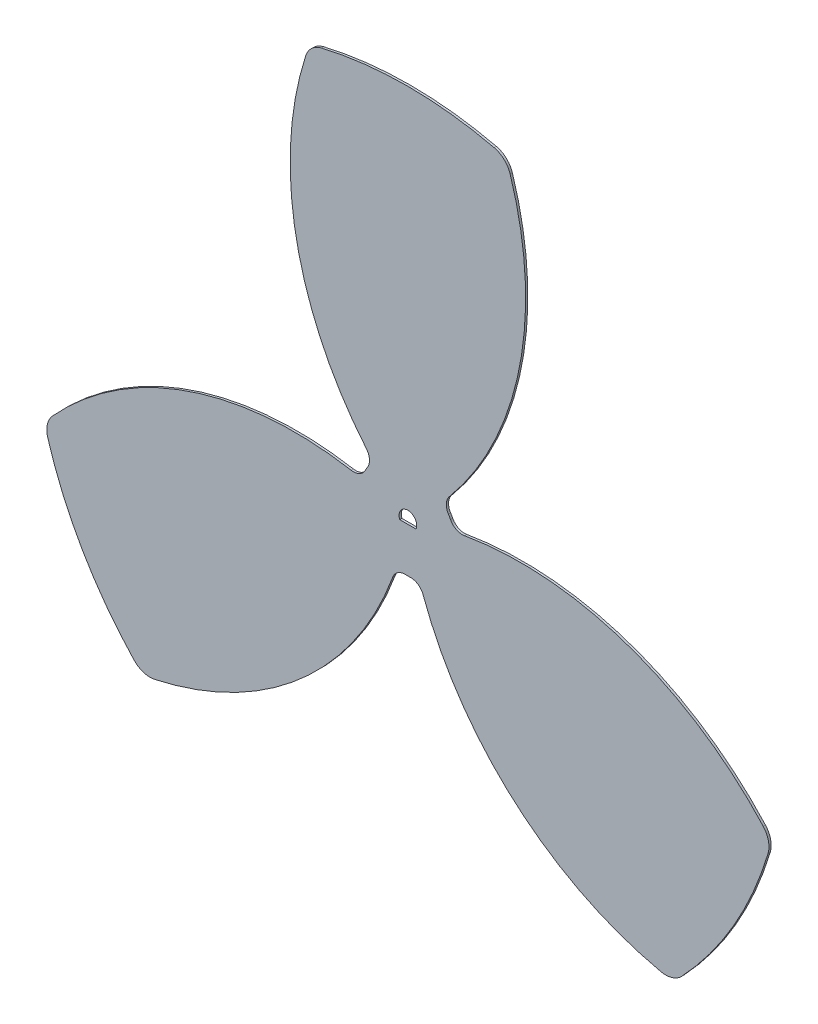
SolidWorks part; units mm, degrees
ref_plane "Plan de face" through (0, 0, 0) normal (0, 0, 1) x (1, 0, 0)
ref_plane "Plan de dessus" through (0, 0, 0) normal (0, 1, 0) x (1, 0, 0)
ref_plane "Plan de droite" through (0, 0, 0) normal (1, 0, 0) x (0, 0, -1)
sketch "Esquisse2" plane through (0, 0, 0) normal (0, 0, 1) x (1, 0, 0)
  line L0 (-43.229, 36.5855) -> (-43.229, 206.5855)
  circle A0 centre (-43.229, 36.5855) radius 21.7168
  arc A1 (1.1818, 200.682) -> (-87.6398, 200.682) centre (-43.229, 36.5855) ccw
  arc A2 (-87.6398, 200.682) -> (-43.229, 36.5855) centre (51.7427, 150.3464) ccw
  arc A3 (1.1818, 200.682) -> (-43.229, 36.5855) centre (-138.2007, 150.3464) cw
  arc A4 (121.0882, -7.0019) -> (-43.229, 36.5855) centre (7.805, -102.5428) ccw
  arc A5 (76.6774, -83.9237) -> (121.0882, -7.0019) centre (-43.229, 36.5855) ccw
  arc A6 (76.6774, -83.9237) -> (-43.229, 36.5855) centre (102.7767, 61.9529) cw
  arc A7 (-163.1354, -83.9237) -> (-43.229, 36.5855) centre (-189.2347, 61.9529) ccw
  arc A8 (-207.5462, -7.0019) -> (-163.1354, -83.9237) centre (-43.229, 36.5855) ccw
  arc A9 (-207.5462, -7.0019) -> (-43.229, 36.5855) centre (-94.263, -102.5428) cw
  point P18 (-43.229, 36.5855)
  dimension "D1" = 3
  dimension "D2" = 170
extrude "Boss.-Extru.1" add sketch "Esquisse2" along normal blind 1 contours A9 A8 A7 A0 | A6 A5 A4 A0 | A3 A1 L0 A0 | A1 A2 A0 L0 | A9 A0 A7 | A6 A0 A4 | A7 A0 A6 | A0 A9 A2 | A0 A2 L0 | A3 A0 L0 | A4 A0 A3
sketch "Esquisse4" plane through (0, 0, 0) normal (0, 0, -1) x (-1, 0, 0)
  line L0 (43.229, 14.8687) -> (43.229, 206.5855) construction
  line L1 (-103.9953, -48.4145) -> (62.0363, 47.4439) construction
  line L2 (46.9371, 35.0855) -> (39.5209, 35.0855)
  arc A0 (37.9538, 15.5192) -> (48.5042, 15.5192) centre (43.229, 36.5855) ccw construction
  arc A2 (39.5209, 35.0855) -> (46.9371, 35.0855) centre (43.229, 36.5855) cw
  arc A5 (87.6398, 200.682) -> (-1.1818, 200.682) centre (43.229, 36.5855) ccw construction
  arc A6 (-121.0882, -7.0019) -> (-76.6774, -83.9237) centre (43.229, 36.5855) ccw construction
  arc A7 (64.1106, 42.5502) -> (58.8354, 51.6871) centre (43.229, 36.5855) ccw construction
  point P16 (43.229, 36.5855)
  point P17 (43.229, 40.5855)
  dimension "D1" = 5.5
  dimension "D2" = 7.4162
  dimension "D3" = 4
extrude "Enlèv. mat.-Extru.2" cut sketch "Esquisse4" against normal through all
fillet "Congé2" radius 10 6 edges at (121.0882, -7.0019, 0.5) (76.6774, -83.9237, 0.5) (-163.1354, -83.9237, 0.5) (-207.5462, -7.0019, 0.5) (-87.6398, 200.682, 0.5) (1.1818, 200.682, 0.5)
fillet "Congé3" radius 6 2 edges at (-58.8354, 51.6871, 0.5) (-64.1106, 42.5502, 0.5)
fillet "Congé4" radius 6 2 edges at (-22.3474, 42.5502, 0.5) (-27.6226, 51.6871, 0.5)
fillet "Congé5" radius 6 2 edges at (-48.5042, 15.5192, 0.5) (-37.9538, 15.5192, 0.5)
